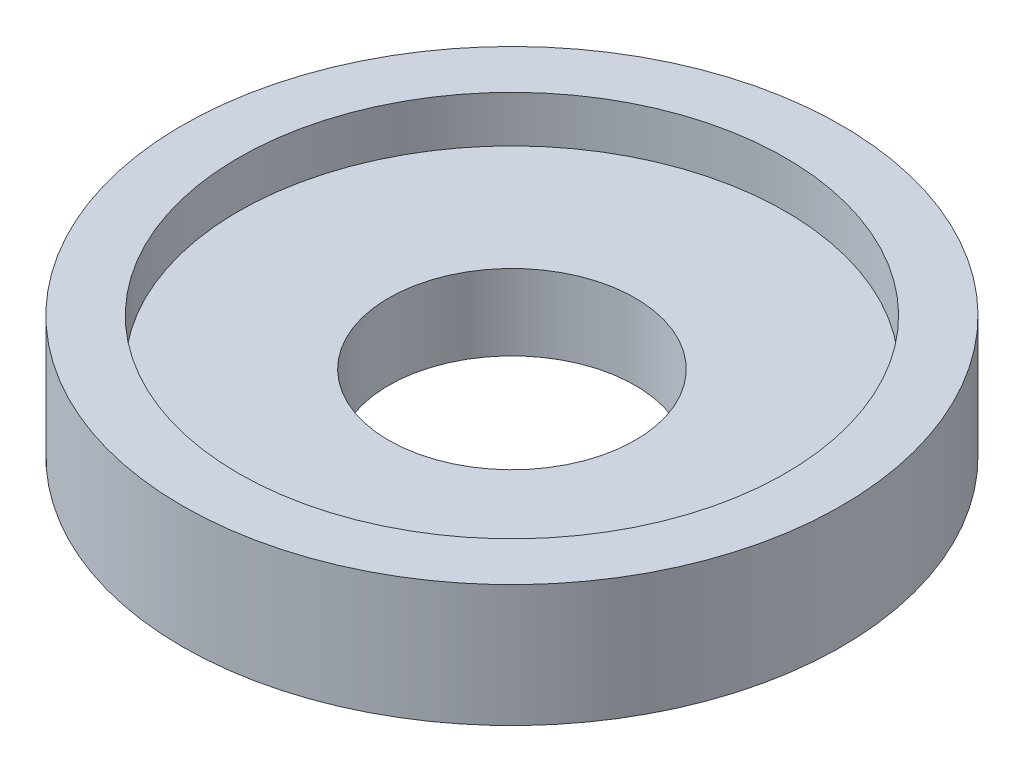
SolidWorks part; units mm, degrees
ref_plane "Front Plane" through (0, 0, 0) normal (0, 0, 1) x (1, 0, 0)
ref_plane "Top Plane" through (0, 0, 0) normal (0, 1, 0) x (1, 0, 0)
ref_plane "Right Plane" through (0, 0, 0) normal (1, 0, 0) x (0, 0, -1)
sketch "Sketch1" plane through (0, 0, 0) normal (0, 1, 0) x (1, 0, 0)
  circle A0 centre (0, 0) radius 13.5
  circle A1 centre (0, 0) radius 5.05
  dimension "D1" = 27
  dimension "D2" = 10.1
extrude "Boss-Extrude1" add sketch "Sketch1" along normal blind 5
sketch "Sketch2" plane through (0, 5, 0) normal (0, 1, 0) x (1, 0, 0)
  circle A0 centre (0, 0) radius 11.2
  dimension "D1" = 22.4
extrude "Cut-Extrude1" cut sketch "Sketch2" against normal blind 1.9
